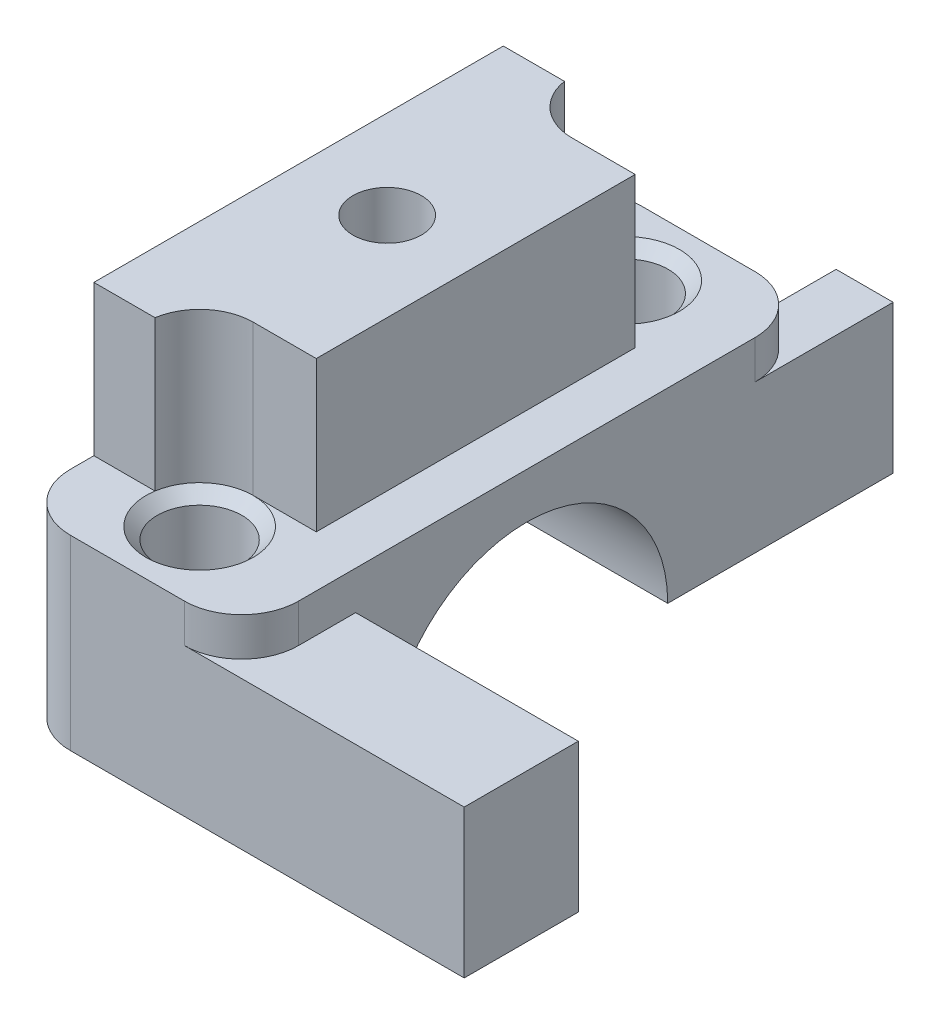
SolidWorks part; units mm, degrees
ref_plane "Front Plane" through (0, 0, 0) normal (0, 0, 1) x (1, 0, 0)
ref_plane "Top Plane" through (0, 0, 0) normal (0, 1, 0) x (1, 0, 0)
ref_plane "Right Plane" through (0, 0, 0) normal (1, 0, 0) x (0, 0, -1)
sketch "Sketch1" plane through (-19.9121, 0, 0) normal (1, 0, 0) x (0, 0, -1)
  line L0 (-57.5, -2.15) -> (-57.5, 12.1967) construction
  line L1 (-7.5, 12.0467) -> (-7.5, -2.15) construction
  line L2 (-44.8458, 12.1967) -> (-52.5, 12.1967)
  line L3 (-7.5, 12.1967) -> (-20.1533, 12.1967)
  line L4 (-7.5, 28.5433) -> (-7.5, 12.1967)
  line L5 (-57.5, -2.15) -> (-57.5, 12.0467) construction
  line L6 (-57.5, 12.1967) -> (-57.5, 28.5433)
  line L7 (-32.5, 24.5433) -> (-20.2164, 24.5433) construction
  line L8 (-57.5, 28.5433) -> (-7.5, 28.5433)
  line L9 (-32.5, 28.5433) -> (-20.2164, 28.5433) construction
  line L10 (-7.5, 12.1967) -> (-7.5, -2.15) construction
  line L11 (-20.1533, 12.1967) -> (-44.8467, 12.1967) construction
  line L12 (-44.8467, 12.1967) -> (-57.5, 12.1967)
  arc A0 (-44.8458, 12.0467) -> (-20.1542, 12.0467) centre (-32.5, 12.1967) ccw construction
  arc A1 (-44.8458, 12.0467) -> (-20.1542, 12.0467) centre (-32.5, 12.1967) ccw construction
  arc A2 (-20.1542, 12.0467) -> (-44.8458, 12.0467) centre (-32.5, 12.1967) ccw
  arc A3 (-44.8458, 12.0467) -> (-20.1542, 12.0467) centre (-32.5, 12.1967) ccw construction
  dimension "D1" = 0.15
  dimension "D2" = 4
extrude "Boss-Extrude1" add sketch "Sketch1" against normal up to surface (20 mm away) contours A2 L3 L4 L8 L6 L12
fillet "Fillet1" radius 5 4 edges at (-19.9121, 20.37, 7.5) (-19.9121, 20.37, 57.5) (-39.9121, 20.37, 7.5) (-39.9121, 20.37, 57.5)
sketch "Sketch2" plane through (0, 28.5433, 0) normal (0, 1, 0) x (1, 0, 0)
  circle A0 centre (-29.9121, -51.1729) radius 2.2 construction
  circle A1 centre (-29.9121, -51.1729) radius 2.2
  circle A2 centre (-29.9121, -13.8271) radius 2.2 construction
  circle A3 centre (-29.9121, -13.8271) radius 2.2
extrude "Cut-Extrude1" cut sketch "Sketch2" against normal through all both and the other way through all
sketch "Sketch3" plane through (0, 28.5433, 0) normal (0, 1, 0) x (1, 0, 0)
  circle A0 centre (-29.9121, -51.1729) radius 2.2 construction
  circle A1 centre (-29.9121, -51.1729) radius 2.2 construction
  circle A2 centre (-29.9121, -13.8271) radius 2.2 construction
  circle A3 centre (-29.9121, -13.8271) radius 2.2 construction
  circle A4 centre (-29.9121, -51.1729) radius 3.5 construction
  circle A5 centre (-29.9121, -51.1729) radius 3.7
  circle A6 centre (-29.9121, -13.8271) radius 3.7
  dimension "D1" = 7
  dimension "D2" = 0.2
extrude "Cut-Extrude2" cut sketch "Sketch3" against normal offset from surface (8.8467 mm away) 7.5 up to face at (-29.9121, 12.1967, 53.3729)
chamfer "Chamfer2" distance 1 angle 45 2 edges at (-29.9121, 28.5433, 17.5271) (-29.9121, 28.5433, 54.8729)
sketch "Sketch4" plane through (0, 28.5433, 0) normal (0, 1, 0) x (1, 0, 0)
  line L0 (-42.4121, 0) -> (-27.5713, 0) construction
  line L2 (-39.9121, -0.4) -> (-19.9121, -0.4)
  line L4 (-39.9121, -12.5) -> (-39.9121, -52.5) construction
  line L5 (0, -69.3863) -> (0, -35.7236) construction
  line L7 (-34.9121, -57.5) -> (-24.9121, -57.5) construction
  line L8 (-34.9121, -57.5) -> (-0.4, -57.5)
  line L9 (-42.4121, -0.4) -> (-27.5713, -0.4) construction
  line L10 (-19.9121, -52.5) -> (-19.9121, -12.5) construction
  line L11 (-19.9121, -52.5) -> (-19.9121, -0.4)
  line L12 (-19.9121, -47.5) -> (-0.4, -47.5)
  line L13 (-0.4, -57.5) -> (-0.4, -47.5)
  line L14 (-0.4, -69.3863) -> (-0.4, -35.7236) construction
  line L15 (-39.9121, -0.4) -> (-39.9121, -59)
  line L20 (-19.9121, -52.5) -> (-19.9121, -12.5)
  line L21 (-24.9121, -7.5) -> (-34.9121, -7.5)
  line L22 (-39.9121, -12.5) -> (-39.9121, -52.5)
  line L23 (-34.9121, -57.5) -> (-24.9121, -57.5)
  line L24 (-19.9121, -52.5) -> (-19.9121, -12.5)
  line L25 (-24.9121, -7.5) -> (-34.9121, -7.5)
  line L26 (-39.9121, -12.5) -> (-39.9121, -52.5)
  line L27 (-34.9121, -57.5) -> (-24.9121, -57.5)
  line L28 (-42.4121, 0) -> (-27.5713, 0) construction
  line L29 (-42.4121, 61.0375) -> (-42.4121, -61.0375) construction
  line L31 (-24.9121, -7.5) -> (-24.9121, -0.4)
  arc A4 (-19.9121, -12.5) -> (-24.9121, -7.5) centre (-24.9121, -12.5) ccw
  arc A5 (-34.9121, -7.5) -> (-39.9121, -12.5) centre (-34.9121, -12.5) ccw
  arc A6 (-39.9121, -52.5) -> (-34.9121, -57.5) centre (-34.9121, -52.5) ccw
  arc A7 (-24.9121, -57.5) -> (-19.9121, -52.5) centre (-24.9121, -52.5) ccw
  arc A8 (-19.9121, -12.5) -> (-24.9121, -7.5) centre (-24.9121, -12.5) ccw
  arc A9 (-34.9121, -7.5) -> (-39.9121, -12.5) centre (-34.9121, -12.5) ccw
  arc A10 (-39.9121, -52.5) -> (-34.9121, -57.5) centre (-34.9121, -52.5) ccw
  arc A11 (-24.9121, -57.5) -> (-19.9121, -52.5) centre (-24.9121, -52.5) ccw
  point P38 (-42.4121, 0)
  line M3 (-19.9121, -52.5) -> (-19.9121, -12.5)
  arc M4 (-19.9121, -12.5) -> (-24.9121, -7.5) centre (-24.9121, -12.5) ccw
  arc M10 (-24.9121, -57.5) -> (-19.9121, -52.5) centre (-24.9121, -52.5) ccw
  dimension "D2" = 10
  dimension "D1" = 0.4
  dimension "D3" = 0.4
  dimension "D4" = 0
extrude "Boss-Extrude2" add sketch "Sketch4" against normal up to surface (12.9717 mm away) from offset 3.375 contours L8 L13 L12 M3 M10 | L31 L11 L2 M4 up to face at (-29.9121, 12.1967, 53.3729) offset against normal yes
sketch "Sketch5" plane through (0, 28.5433, 0) normal (0, 1, 0) x (1, 0, 0)
  line L0 (-19.9121, -32.5) -> (-39.9121, -32.5) construction
  line L1 (-19.9121, -52.5) -> (-19.9121, -12.5) construction
  line L2 (-39.9121, -12.5) -> (-39.9121, -52.5) construction
  line L3 (-24.3888, -48.3347) -> (-24.3888, -19.6944) construction
  line L4 (-24.3888, -50.4375) -> (-39.9121, -50.4375)
  line L5 (-24.3888, -50.4375) -> (-24.3888, -14.5625)
  line L6 (-24.3888, -14.5625) -> (-39.9121, -14.5625)
  line L7 (-39.9121, -50.4375) -> (-39.9121, -14.5625)
  line L8 (-24.3888, -50.4375) -> (-39.9121, -14.5625) construction
  line L9 (-24.3888, -14.5625) -> (-39.9121, -50.4375) construction
  line L10 (-29.9121, -18.5271) -> (-24.3888, -18.5271)
  line L11 (-29.9121, -46.4729) -> (-24.3888, -46.4729)
  circle A0 centre (-29.9121, -13.8271) radius 4.7 construction
  circle A1 centre (-29.9121, -13.8271) radius 4.7
  circle A2 centre (-29.9121, -51.1729) radius 4.7 construction
  circle A3 centre (-29.9121, -51.1729) radius 4.7
  point P6 (-32.1504, -32.5)
  circle M1 centre (-29.9121, -13.8271) radius 4.7
  circle M2 centre (-29.9121, -51.1729) radius 4.7
  line M7 (-39.9121, -12.5) -> (-39.9121, -52.5)
extrude "Boss-Extrude3" add sketch "Sketch5" along normal up to surface (13.1533 mm away) contours L5 L6 L4 M1 M7 M2
sketch "Sketch6" plane through (0, 41.6967, 0) normal (0, 1, 0) x (1, 0, 0)
  line L0 (-24.3888, -32.5) -> (-39.9121, -32.5) construction
  line L1 (-24.3888, -18.5271) -> (-24.3888, -46.4729) construction
  line L2 (-39.9121, -50.4375) -> (-39.9121, -14.5625) construction
  circle A0 centre (-32.1504, -32.5) radius 3
  dimension "D1" = 6
extrude "Cut-Extrude3" cut sketch "Sketch6" against normal blind 6.2
sketch "Sketch7" plane through (0, 35.4967, 0) normal (0, 1, 0) x (1, 0, 0)
  circle A0 centre (-32.1504, -32.5) radius 2 construction
  circle A1 centre (-32.1504, -32.5) radius 3
  circle A2 centre (-32.1504, -32.5) radius 3 construction
  circle A3 centre (-32.1504, -32.5) radius 2.2
  dimension "D2" = 4
  dimension "D1" = 0
  dimension "D3" = 0.2
extrude "Cut-Extrude4" cut sketch "Sketch7" against normal through all both and the other way through all
